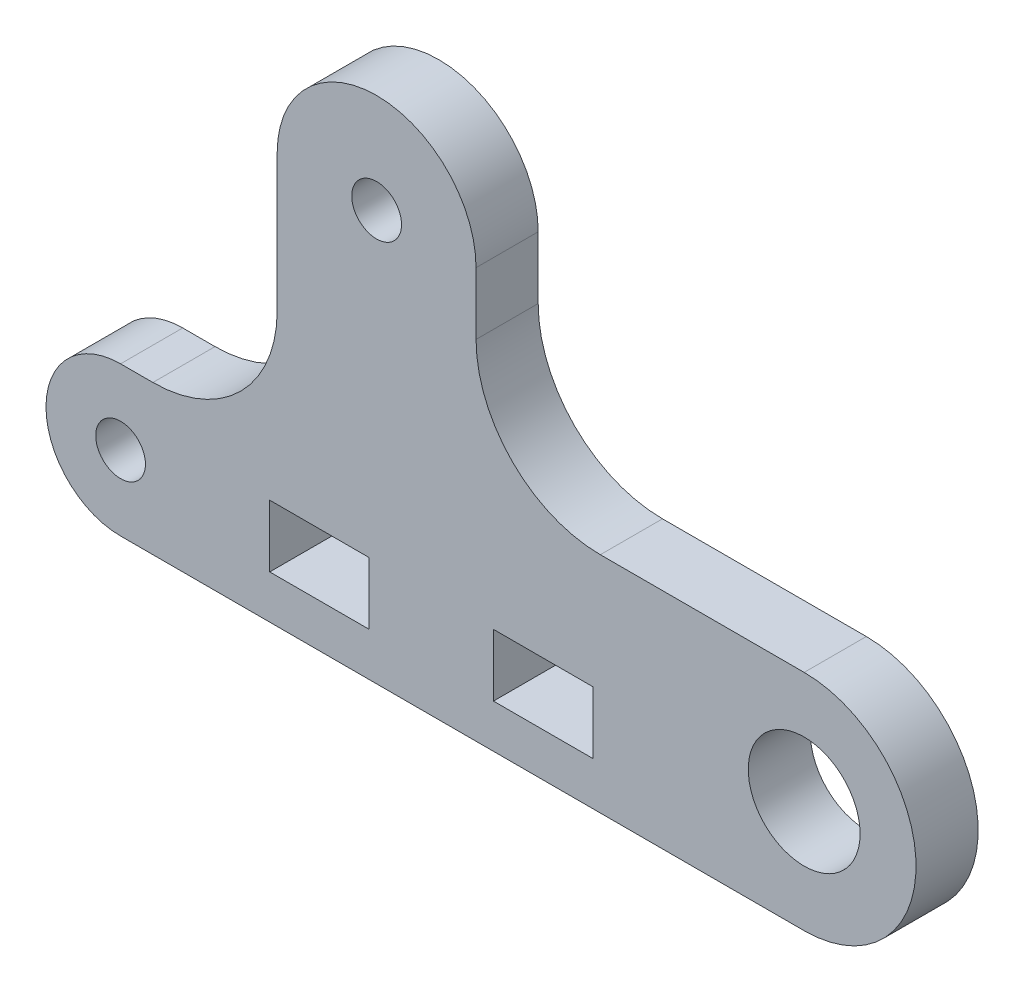
SolidWorks part; units mm, degrees
ref_plane "Front Plane" through (0, 0, 0) normal (0, 0, 1) x (1, 0, 0)
ref_plane "Top Plane" through (0, 0, 0) normal (0, 1, 0) x (1, 0, 0)
ref_plane "Right Plane" through (0, 0, 0) normal (1, 0, 0) x (0, 0, -1)
sketch "Sketch1" plane through (0, 0, 0) normal (0, 0, 1) x (1, 0, 0)
  line L0 (-27.5, 0) -> (27.5, 0)
  line L1 (0, 0) -> (0, 28.6928) construction
  line L2 (-27.5, 12) -> (-24.9, 12)
  line L3 (-14.9, 22) -> (-14.9, 33)
  line L4 (1.1, 33) -> (1.1, 28)
  line L5 (11.1, 18) -> (27.5, 18)
  line L6 (-27.5, 6) -> (-15.5, 6) construction
  line L8 (-15.5, 8.5) -> (-7.5, 8.5)
  line L9 (-15.5, 8.5) -> (-15.5, 3.5)
  line L10 (-15.5, 3.5) -> (-7.5, 3.5)
  line L11 (-7.5, 8.5) -> (-7.5, 3.5)
  line L12 (2.5, 8.5) -> (10.5, 8.5)
  line L13 (2.5, 8.5) -> (2.5, 3.5)
  line L14 (2.5, 3.5) -> (10.5, 3.5)
  line L15 (10.5, 8.5) -> (10.5, 3.5)
  circle A0 centre (27.5, 9) radius 4.5
  circle A1 centre (-27.5, 6) radius 2
  circle A2 centre (-6.9, 33) radius 2.0035
  circle A3 centre (-6.9, 33) radius 8 construction
  arc A4 (27.5, 0) -> (27.5, 18) centre (27.5, 9) ccw
  arc A5 (-27.5, 0) -> (-27.5, 12) centre (-27.5, 6) cw
  arc A6 (-14.9, 33) -> (1.1, 33) centre (-6.9, 33) cw
  arc A7 (1.1, 28) -> (11.1, 18) centre (11.1, 28) ccw
  arc A8 (-24.9, 12) -> (-14.9, 22) centre (-24.9, 22) ccw
  point P25 (-14.9, 12)
  dimension "D2" = 9
  dimension "D3" = 9
  dimension "D4" = 4
  dimension "D5" = 6
  dimension "D7" = 16
  dimension "D9" = 10
  dimension "D1" = 55
  dimension "D6" = 33
  dimension "D8" = 6.9
  dimension "D10" = 12
  dimension "D11" = 8
  dimension "D12" = 5
  dimension "D13" = 10
extrude "Boss-Extrude1" add sketch "Sketch1" along normal mid plane 5
